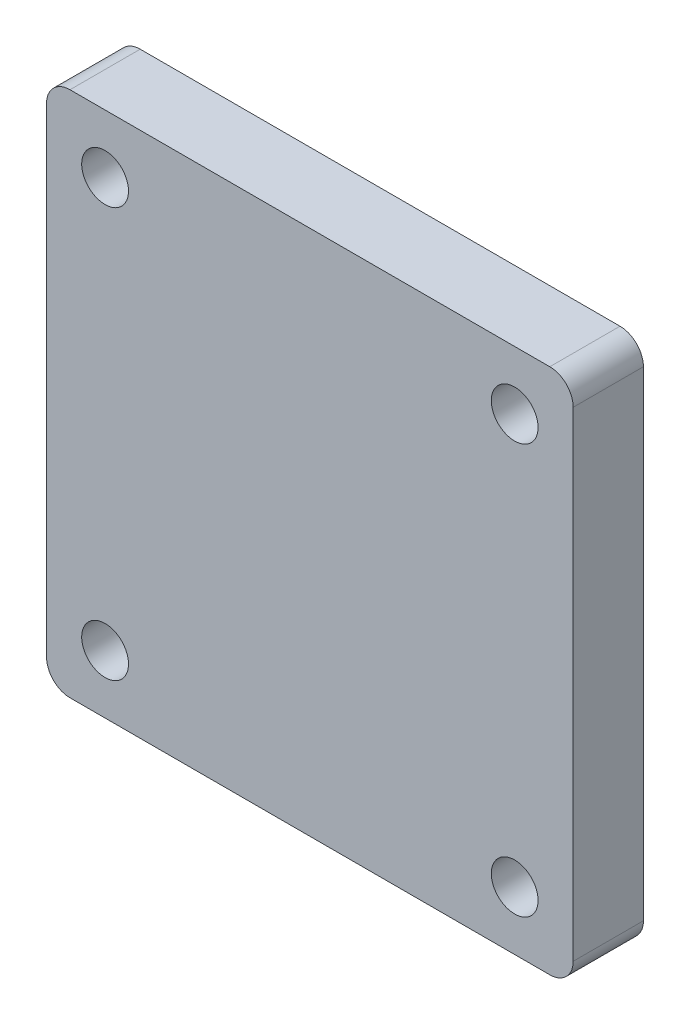
SolidWorks part; units mm, degrees
ref_plane "Front Plane" through (0, 0, 0) normal (0, 0, 1) x (1, 0, 0)
ref_plane "Top Plane" through (0, 0, 0) normal (0, 1, 0) x (1, 0, 0)
ref_plane "Right Plane" through (0, 0, 0) normal (1, 0, 0) x (0, 0, -1)
sketch "Sketch1" plane through (0, 0, 0) normal (0, 0, 1) x (1, 0, 0)
  line L1 (0, 0) -> (22.5, 0)
  line L2 (0, 0) -> (0, 22.5)
  line L3 (0, 22.5) -> (22.5, 22.5)
  line L4 (22.5, 0) -> (22.5, 22.5)
  line L5 (2.5, 20) -> (20, 20) construction
  line L6 (2.5, 20) -> (2.5, 2.5) construction
  line L7 (2.5, 2.5) -> (20, 2.5) construction
  line L8 (20, 20) -> (20, 2.5) construction
  circle A0 centre (2.5, 20) radius 1
  circle A1 centre (20, 20) radius 1
  circle A2 centre (20, 2.5) radius 1
  circle A3 centre (2.5, 2.5) radius 1
  dimension "D7" = 2
  dimension "D8" = 2
  dimension "D9" = 2
  dimension "D10" = 2
  dimension "D1" = 22.5
  dimension "D2" = 22.5
  dimension "D3" = 17.5
  dimension "D4" = 17.5
  dimension "D5" = 2.5
  dimension "D6" = 2.5
extrude "Boss-Extrude1" add sketch "Sketch1" along normal blind 3
fillet "Fillet1" radius 1 4 edges at (22.5, 22.5, 1.5) (22.5, 0, 1.5) (0, 0, 1.5) (0, 22.5, 1.5)
